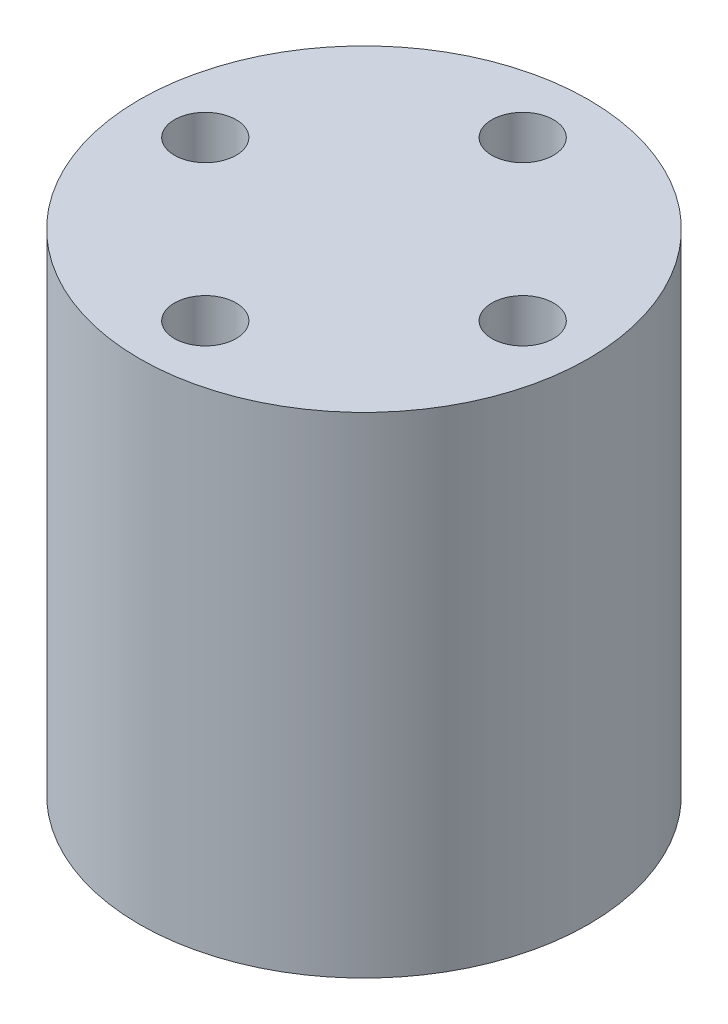
SolidWorks part; units mm, degrees
ref_plane "Front" through (0, 0, 0) normal (0, 0, 1) x (1, 0, 0)
ref_plane "Top" through (0, 0, 0) normal (0, 1, 0) x (1, 0, 0)
ref_plane "Right" through (0, 0, 0) normal (1, 0, 0) x (0, 0, -1)
sketch "Sketch1" plane through (0, 0, 0) normal (0, 1, 0) x (1, 0, 0)
  circle A0 centre (0, 0) radius 16
  circle A1 centre (0, 0) radius 11.3137
  circle A2 centre (0, -11.3137) radius 2.2
  circle A3 centre (11.3137, 0) radius 2.2
  circle A4 centre (0, 11.3137) radius 2.2
  circle A5 centre (-11.3137, 0) radius 2.2
extrude "Boss-Extrude1" add sketch "Sketch1" along normal blind 34.925 contours A5 A1 A2 A3 A4 | A0 A5 A1 A4 A3 A2
